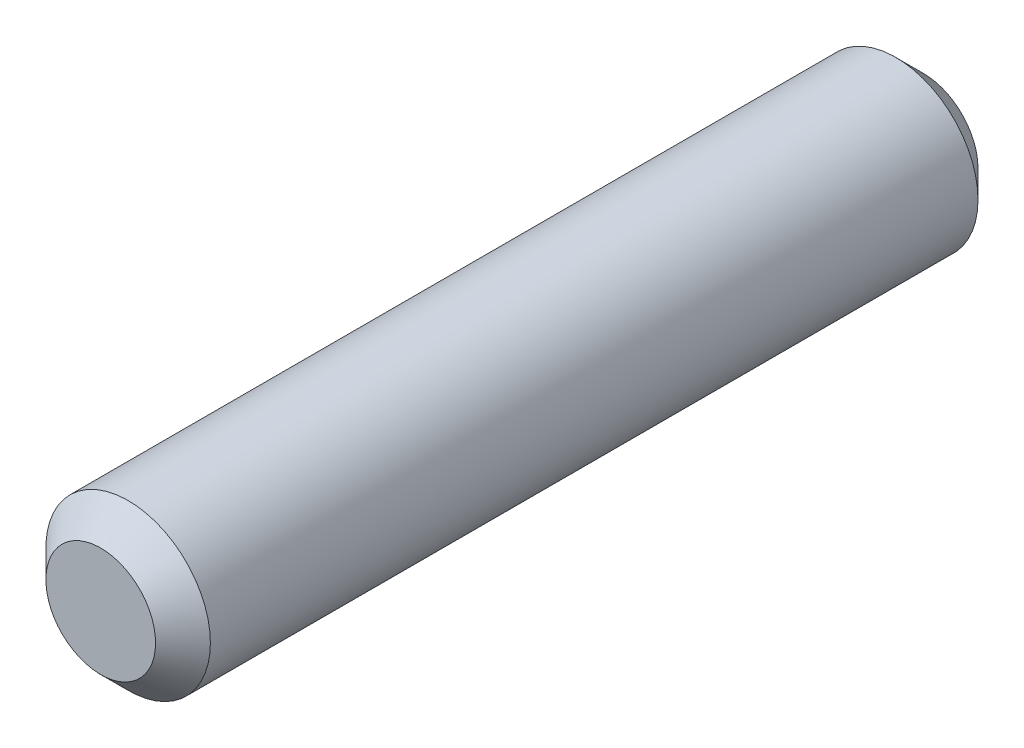
SolidWorks part; units mm, degrees
ref_plane "Front Plane" through (0, 0, 0) normal (0, 0, 1) x (1, 0, 0)
ref_plane "Top Plane" through (0, 0, 0) normal (0, 1, 0) x (1, 0, 0)
ref_plane "Right Plane" through (0, 0, 0) normal (1, 0, 0) x (0, 0, -1)
sketch "Sketch1" plane through (0, 0, 0) normal (0, 0, 1) x (1, 0, 0)
  circle A0 centre (0, 0) radius 1.5
  dimension "D1" = 3
extrude "Boss-Extrude2" add sketch "Sketch1" along normal blind 15
chamfer "Chamfer2" distance 0.5 angle 45 2 edges at (1.5, 0, 15) (1.5, 0, 0)
